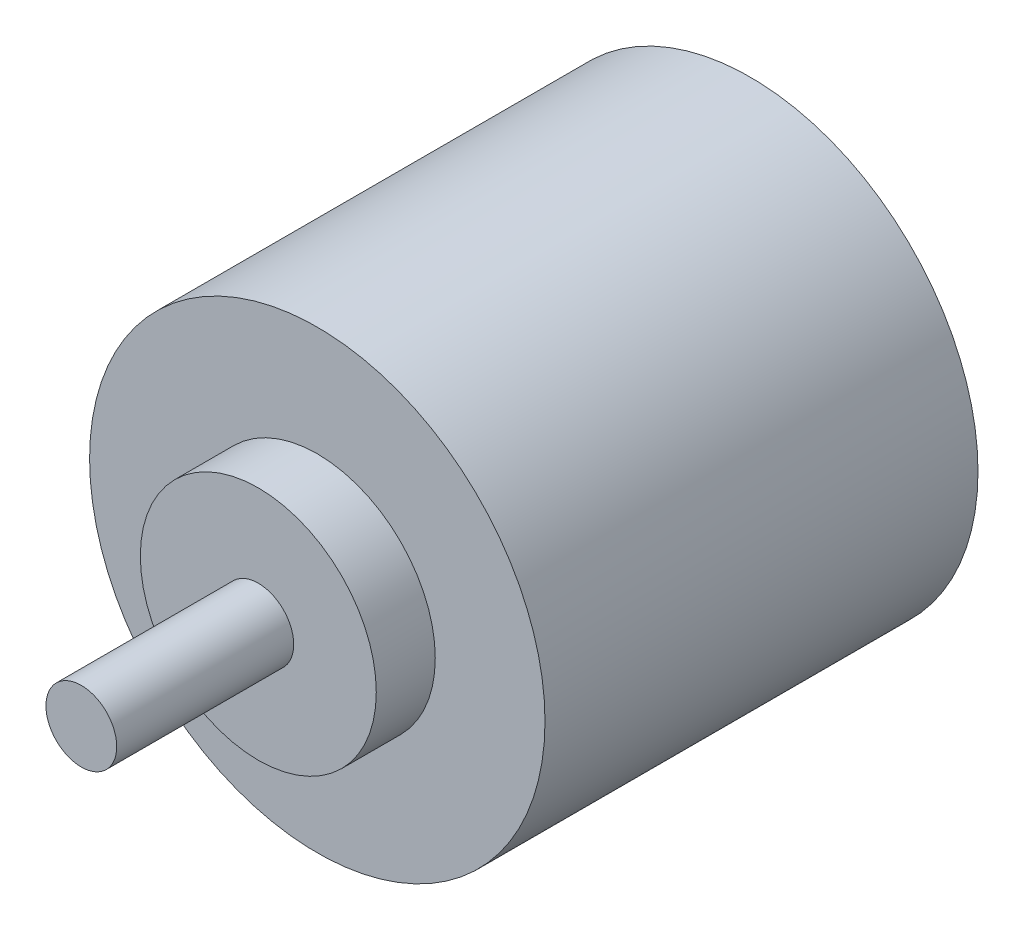
SolidWorks part; units mm, degrees
ref_plane "Front Plane" through (0, 0, 0) normal (0, 0, 1) x (1, 0, 0)
ref_plane "Top Plane" through (0, 0, 0) normal (0, 1, 0) x (1, 0, 0)
ref_plane "Right Plane" through (0, 0, 0) normal (1, 0, 0) x (0, 0, -1)
sketch "Sketch1" plane through (0, 0, 0) normal (0, 0, 1) x (1, 0, 0)
  circle A0 centre (-14.1274, 5.3793) radius 19.3
  dimension "D1" = 38.6
extrude "Boss-Extrude1" add sketch "Sketch1" along normal blind 36.7
sketch "Sketch3" plane through (0, 0, 36.7) normal (0, 0, 1) x (1, 0, 0)
  circle A0 centre (-14.1274, 5.3793) radius 10
  circle A1 centre (-14.1274, 5.3793) radius 19.3 construction
  dimension "D1" = 20
  dimension "D2" = 0
extrude "Boss-Extrude2" add sketch "Sketch3" along normal blind 5
sketch "Sketch4" plane through (0, 0, 41.7) normal (0, 0, 1) x (1, 0, 0)
  circle A0 centre (-14.1274, 5.3793) radius 3
  circle A1 centre (-14.1274, 5.3793) radius 10 construction
  dimension "D1" = 6
  dimension "D2" = 0
extrude "Boss-Extrude3" add sketch "Sketch4" along normal blind 15
